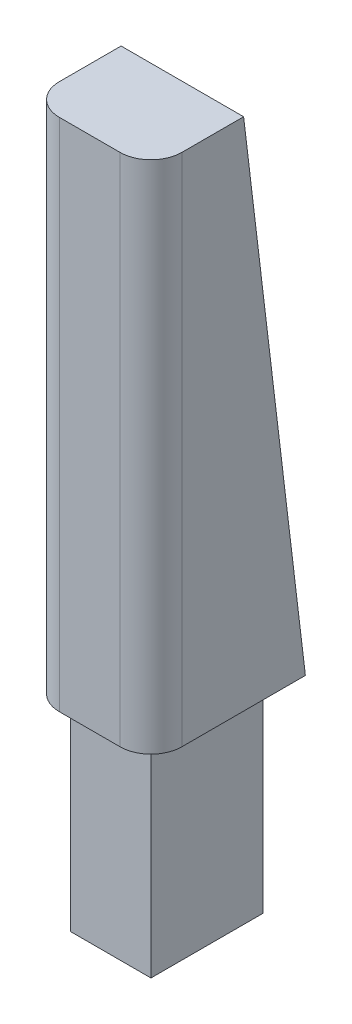
SolidWorks part; units mm, degrees
ref_plane "Front Plane" through (0, 0, 0) normal (0, 0, 1) x (1, 0, 0)
ref_plane "Top Plane" through (0, 0, 0) normal (0, 1, 0) x (1, 0, 0)
ref_plane "Right Plane" through (0, 0, 0) normal (1, 0, 0) x (0, 0, -1)
sketch "Sketch1" plane through (0, 0, 0) normal (0, 1, 0) x (1, 0, 0)
  line L1 (-3.9, -5.45) -> (3.9, -5.45)
  line L2 (-3.9, -5.45) -> (-3.9, 5.45)
  line L3 (-3.9, 5.45) -> (3.9, 5.45)
  line L4 (3.9, -5.45) -> (3.9, 5.45)
  line L5 (-3.9, -5.45) -> (3.9, 5.45) construction
  line L6 (-3.9, 5.45) -> (3.9, -5.45) construction
  point P0 (0, 0)
  dimension "D1" = 7.8
  dimension "D2" = 10.9
extrude "Boss-Extrude1" add sketch "Sketch1" along normal blind 20
sketch "Sketch2" plane through (0, 20, 0) normal (0, 1, 0) x (1, 0, 0)
  line L1 (-5.95, -7.5) -> (5.95, -7.5)
  line L2 (-5.95, -7.5) -> (-5.95, 7.5)
  line L3 (-5.95, 7.5) -> (5.95, 7.5)
  line L4 (5.95, -7.5) -> (5.95, 7.5)
  line L5 (-5.95, -7.5) -> (5.95, 7.5) construction
  line L6 (-5.95, 7.5) -> (5.95, -7.5) construction
  point P0 (0, 0)
  dimension "D1" = 15
  dimension "D2" = 11.9
extrude "Boss-Extrude2" add sketch "Sketch2" along normal blind 50
sketch "Sketch3" plane through (-5.95, 0, 0) normal (-1, 0, 0) x (0, 0, 1)
  line L0 (-7.5, 20) -> (-1.5, 70)
  line L1 (-7.5, 70) -> (7.5, 70) construction
  line L2 (-1.5, 70) -> (-7.5, 70)
  line L3 (-7.5, 70) -> (-7.5, 20)
  dimension "D1" = 6
extrude "Cut-Extrude1" cut sketch "Sketch3" against normal through all both and the other way through all
fillet "Fillet1" radius 3 2 edges at (5.95, 45, 7.5) (-5.95, 45, 7.5)
